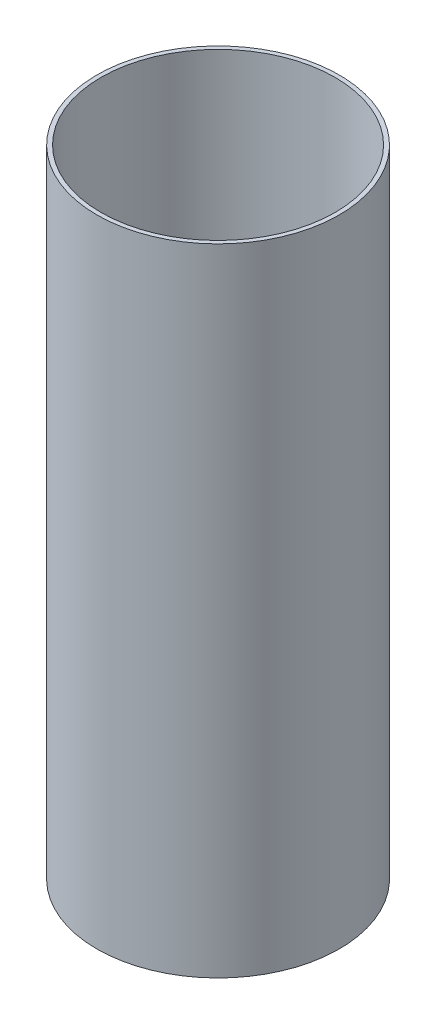
SolidWorks part; units mm, degrees
material "Acrylic (Medium-high impact)"
ref_plane "Front Plane" through (0, 0, 0) normal (0, 0, 1) x (1, 0, 0)
ref_plane "Top Plane" through (0, 0, 0) normal (0, 1, 0) x (1, 0, 0)
ref_plane "Right Plane" through (0, 0, 0) normal (1, 0, 0) x (0, 0, -1)
sketch "Sketch1" plane through (0, 0, 0) normal (0, 1, 0) x (1, 0, 0)
  circle A0 centre (0, 0) radius 92.075
  circle A1 centre (0, 0) radius 88.9
  dimension "D1" = 184.15
  dimension "D2" = 177.8
extrude "Boss-Extrude1" add sketch "Sketch1" along normal mid plane 482.854
ref_plane "Plane1" through (0, 0, 92.075) normal (0, 0, 1) x (1, 0, 0)
sketch "Sketch3" plane through (0, 0, 92.075) normal (0, 0, 1) x (1, 0, 0)
  line L0 (0, -55) -> (0, 55) construction
  line L1 (-92.075, -241.427) -> (92.075, -241.427) construction
  circle A0 centre (0, -235.077) radius 1.4351
  dimension "D1" = 2.8702
  dimension "D2" = 6.35
extrude "Cut-Extrude1" [suppressed] cut sketch "Sketch3" against normal blind 19.304
pattern_circular "CirPattern1" [suppressed] count 12 over 360
mirror "Mirror1" [suppressed] about plane through (0, 0, 0) normal (0, 1, 0)
sketch "Sketch4" [suppressed] plane through (0, 0, 92.075) normal (0, 0, 1) x (1, 0, 0)
  line L0 (0, -55) -> (0, 55) construction
  circle A0 centre (0, -78.359) radius 1.4351
  circle A1 centre (0, 78.359) radius 1.4351
  circle A2 centre (0, 235.077) radius 1.4351 construction
  circle A3 centre (0, -235.077) radius 1.4351 construction
  dimension "D1" = 2.8702
  dimension "D2" = 2.8702
  dimension "D3" = 156.718
  dimension "D4" = 156.718
extrude "Cut-Extrude2" [suppressed] cut sketch "Sketch4" against normal blind 25.146
pattern_circular "CirPattern2" [suppressed] count 3 over 360
